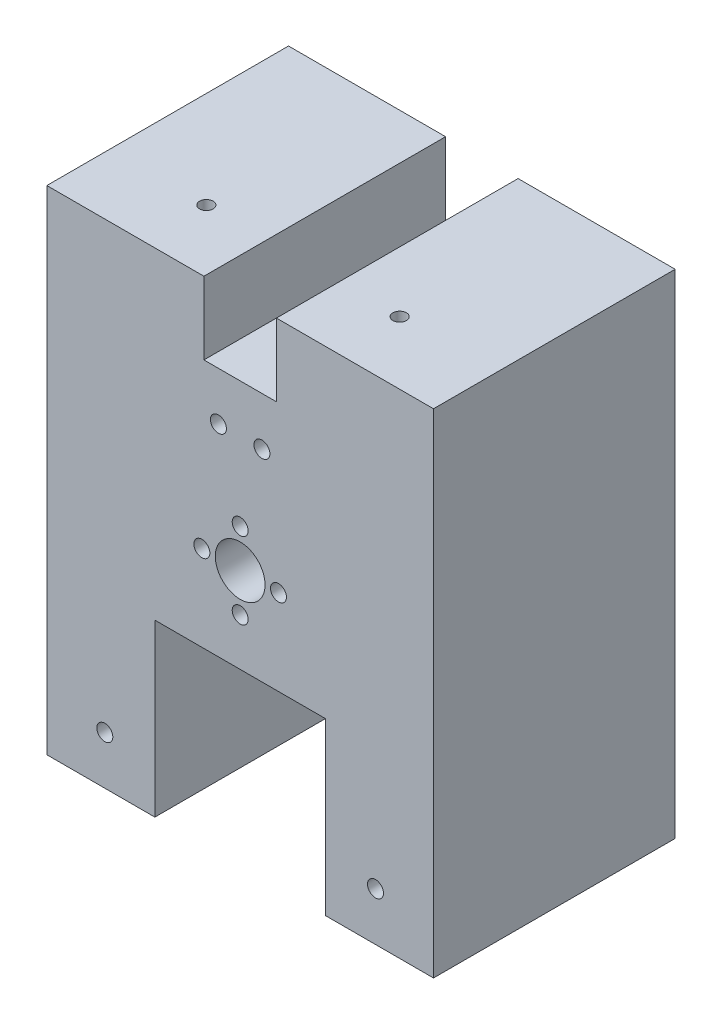
SolidWorks part; units mm, degrees
ref_plane "前视基准面" through (0, 0, 0) normal (0, 0, 1) x (1, 0, 0)
ref_plane "上视基准面" through (0, 0, 0) normal (0, 1, 0) x (1, 0, 0)
ref_plane "右视基准面" through (0, 0, 0) normal (1, 0, 0) x (0, 0, -1)
sketch "草图1" plane through (0, 0, 0) normal (0, 0, 1) x (1, 0, 0)
  line L1 (-40, -51.75) -> (40, -51.75)
  line L2 (-40, -51.75) -> (-40, 51.75)
  line L3 (-40, 51.75) -> (40, 51.75)
  line L4 (40, -51.75) -> (40, 51.75)
  line L5 (-40, -51.75) -> (40, 51.75) construction
  line L6 (-40, 51.75) -> (40, -51.75) construction
  point P0 (0, 0)
  dimension "D1" = 80
  dimension "D2" = 103.5
extrude "凸台-拉伸1" add sketch "草图1" along normal blind 50
sketch "草图2" plane through (0, 0, 50) normal (0, 0, 1) x (1, 0, 0)
  line L0 (-76.3845, -41.75) -> (84.9234, -41.75) construction
  line L1 (-40, -51.75) -> (40, -51.75) construction
  line L2 (-40, 51.75) -> (-40, -51.75) construction
  line L3 (40, -51.75) -> (40, 51.75) construction
  circle A0 centre (25, -41.75) radius 1.65
  circle A1 centre (-25, -41.75) radius 1.65
  dimension "D2" = 3.3
  dimension "D3" = 3.3
  dimension "D4" = 15
  dimension "D5" = 15
  dimension "D1" = 10
extrude "切除-拉伸1" [suppressed] cut sketch "草图2" against normal blind 60
sketch "草图3" plane through (-40, 0, 0) normal (-1, 0, 0) x (0, 0, 1)
  line L0 (25, 51.75) -> (25, -51.75) construction
  line L1 (50, 51.75) -> (0, 51.75) construction
  line L2 (50, -51.75) -> (0, -51.75) construction
  line L4 (15, 18.25) -> (35, 18.25)
  line L5 (15, 18.25) -> (15, 38.25)
  line L6 (15, 38.25) -> (35, 38.25)
  line L7 (35, 18.25) -> (35, 38.25)
  line L8 (15, 18.25) -> (35, 38.25) construction
  line L9 (15, 38.25) -> (35, 18.25) construction
  point P6 (25, 28.25)
  dimension "D1" = 20
  dimension "D2" = 20
  dimension "D3" = 80
extrude "切除-拉伸2" [suppressed] cut sketch "草图3" against normal blind 5000
sketch "草图4" plane through (0, 0, 50) normal (0, 0, 1) x (1, 0, 0)
  line L0 (-30, 28.25) -> (30, 28.25) construction
  line L1 (-40, -51.75) -> (40, -51.75) construction
  circle A0 centre (-30, 28.25) radius 4.1086
  circle A1 centre (30, 28.25) radius 4.4115
  dimension "D1" = 60
  dimension "D2" = 30
  dimension "D3" = 80
extrude "切除-拉伸3" [suppressed] cut sketch "草图4" against normal blind 60
sketch "草图5" plane through (0, 0, 50) normal (0, 0, 1) x (1, 0, 0)
  line L1 (-40, -51.75) -> (40, -51.75) construction
  circle A0 centre (0, 2.75) radius 7.925 construction
  circle A1 centre (7.925, 2.75) radius 1.65
  circle A2 centre (-7.925, 2.75) radius 1.65
  circle A3 centre (0, 10.675) radius 1.65
  circle A4 centre (0, -5.175) radius 1.65
  dimension "D1" = 15.85
  dimension "D2" = 3.3
  dimension "D3" = 3.3
  dimension "D4" = 3.3
  dimension "D5" = 3.3
  dimension "D6" = 54.5
extrude "切除-拉伸4" cut sketch "草图5" against normal blind 60
sketch "草图6" plane through (0, -51.75, 0) normal (0, -1, 0) x (1, 0, 0)
  line L0 (-40, 25) -> (40, 25) construction
  line L1 (-40, 50) -> (-40, 0) construction
  line L2 (40, 50) -> (40, 0) construction
  line L3 (0, 50) -> (0, 0) construction
  line L4 (-40, 50) -> (40, 50) construction
  line L10 (25, 12.5) -> (45, 12.5)
  line L11 (25, 12.5) -> (25, 37.5)
  line L12 (25, 37.5) -> (45, 37.5)
  line L13 (45, 12.5) -> (45, 37.5)
  line L14 (25, 12.5) -> (45, 37.5) construction
  line L15 (25, 37.5) -> (45, 12.5) construction
  point P11 (0, 25)
  point P12 (35, 25)
  dimension "D1" = 25
  dimension "D2" = 20
  dimension "D3" = 90
extrude "切除-拉伸5" [suppressed] cut sketch "草图6" against normal blind 25
mirror "镜向1" [suppressed] about plane through (0, 0, 0) normal (1, 0, 0)
sketch "草图7" plane through (0, 0, 50) normal (0, 0, 1) x (1, 0, 0)
  line L0 (0, 69.5262) -> (0, -82.0784) construction
  line L1 (40, 51.75) -> (-40, 51.75) construction
  line L2 (-7.5, 36.75) -> (7.5, 36.75)
  line L3 (-7.5, 36.75) -> (-7.5, 51.75)
  line L4 (-7.5, 51.75) -> (7.5, 51.75)
  line L5 (7.5, 36.75) -> (7.5, 51.75)
  line L6 (-7.5, 36.75) -> (7.5, 51.75) construction
  line L7 (-7.5, 51.75) -> (7.5, 36.75) construction
  point P3 (0, 44.25)
  dimension "D1" = 15
  dimension "D2" = 15
extrude "切除-拉伸6" cut sketch "草图7" against normal blind 100
sketch "草图8" plane through (0, 0, 50) normal (0, 0, 1) x (1, 0, 0)
  line L0 (0, 53.8631) -> (0, -64.3232) construction
  line L2 (-74.6693, 26.75) -> (84.8631, 26.75) construction
  line L3 (-7.5, 36.75) -> (7.5, 36.75) construction
  circle A1 centre (4.5, 26.75) radius 1.65
  circle A2 centre (-4.5, 26.75) radius 1.65
  dimension "D1" = 10
  dimension "D2" = 3.3
  dimension "D3" = 3.3
  dimension "D4" = 9
  dimension "D5" = 4.5
extrude "切除-拉伸7" cut sketch "草图8" against normal blind 100
sketch "草图9" plane through (0, 0, 50) normal (0, 0, 1) x (1, 0, 0)
  circle A0 centre (0, 2.75) radius 5.15
  dimension "D1" = 10.3
extrude "切除-拉伸8" cut sketch "草图9" against normal blind 1000
sketch "草图10" plane through (0, 0, 50) normal (0, 0, 1) x (1, 0, 0)
  line L0 (0, -37.7121) -> (0, -70.8409) construction
  line L2 (-40, -50.25) -> (40, -50.25)
  line L3 (-40, -50.25) -> (-40, -51.75)
  line L4 (-40, -51.75) -> (40, -51.75)
  line L5 (40, -50.25) -> (40, -51.75)
  line L6 (-40, -50.25) -> (40, -51.75) construction
  line L7 (-40, -51.75) -> (40, -50.25) construction
  point P3 (0, -51)
  dimension "D1" = 1.5
extrude "切除-拉伸9" cut sketch "草图10" against normal blind 10000
sketch "草图11" plane through (0, 0, 50) normal (0, 0, 1) x (1, 0, 0)
  line L0 (0, -18.4649) -> (0, -72.6336) construction
  line L1 (40, -50.25) -> (-40, -50.25) construction
  line L2 (-17.65, -14.95) -> (17.65, -14.95)
  line L3 (-17.65, -14.95) -> (-17.65, -50.25)
  line L4 (-17.65, -50.25) -> (17.65, -50.25)
  line L5 (17.65, -14.95) -> (17.65, -50.25)
  line L6 (-17.65, -14.95) -> (17.65, -50.25) construction
  line L7 (-17.65, -50.25) -> (17.65, -14.95) construction
  point P3 (0, -32.6)
  dimension "D1" = 35.3
  dimension "D2" = 35.3
extrude "切除-拉伸10" cut sketch "草图11" against normal blind 1000
sketch "草图12" plane through (0, 0, 50) normal (0, 0, 1) x (1, 0, 0)
  line L0 (-62.9185, -40.25) -> (67.963, -40.25) construction
  line L1 (28, -13.0536) -> (28, -54.877) construction
  line L2 (-28, -11.3109) -> (-28, -54.2349) construction
  line L3 (40, -50.25) -> (40, 51.75) construction
  line L4 (-40, 51.75) -> (-40, -50.25) construction
  line L5 (40, -50.25) -> (17.65, -50.25) construction
  circle A0 centre (28, -40.25) radius 1.65
  circle A2 centre (-28, -40.25) radius 1.65
  dimension "D4" = 3.3
  dimension "D5" = 3.3
  dimension "D1" = 12
  dimension "D2" = 12
  dimension "D3" = 10
extrude "切除-拉伸11" cut sketch "草图12" against normal blind 1000
sketch "草图14" plane through (0, 51.75, 0) normal (0, 1, 0) x (1, 0, 0)
  line L0 (40, -50) -> (40, 0) construction
  line L1 (40, -50) -> (7.5, -50) construction
  line L2 (-7.5, -50) -> (-40, -50) construction
  line L3 (-40, -50) -> (-40, 0) construction
  circle A0 centre (20, -37) radius 1.4
  circle A1 centre (-20, -37) radius 1.4
  dimension "D1" = 2.8
  dimension "D2" = 2.8
  dimension "D3" = 20
  dimension "D4" = 13
  dimension "D5" = 13
  dimension "D6" = 20
extrude "切除-拉伸12" cut sketch "草图14" against normal blind 35
